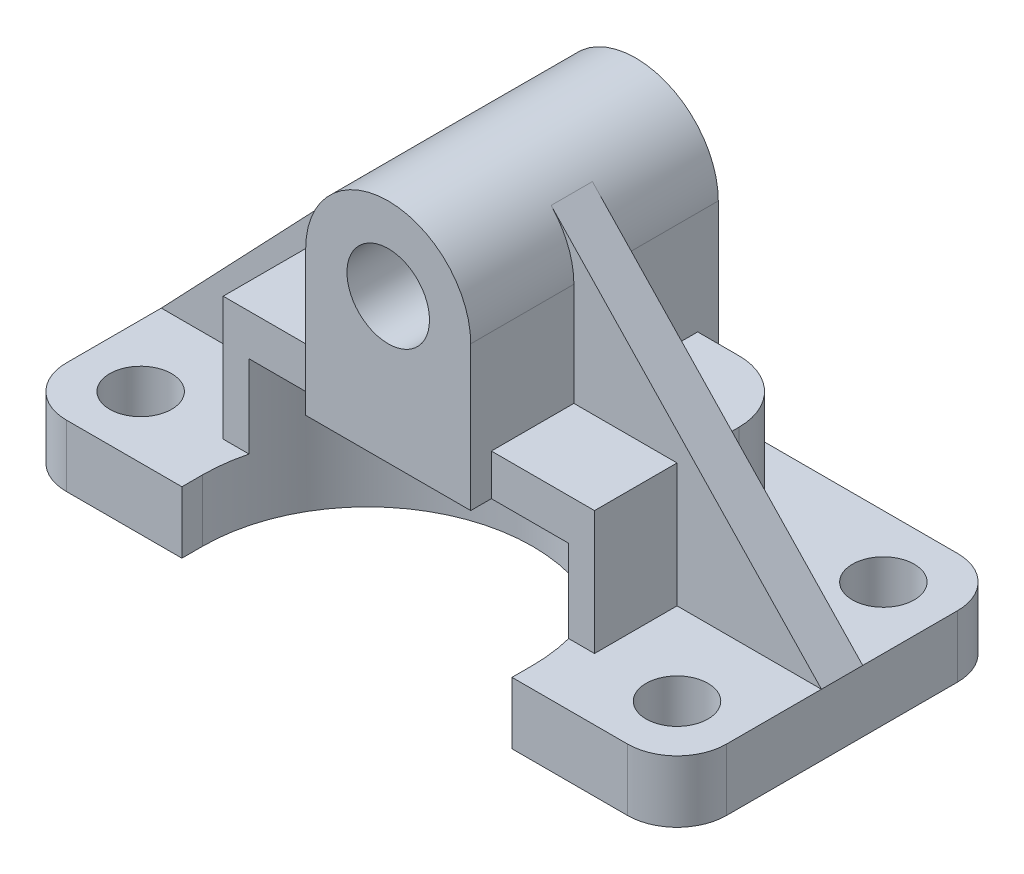
SolidWorks part; units mm, degrees
ref_plane "前视基准面" through (0, 0, 0) normal (0, 0, 1) x (1, 0, 0)
ref_plane "上视基准面" through (0, 0, 0) normal (0, 1, 0) x (1, 0, 0)
ref_plane "右视基准面" through (0, 0, 0) normal (1, 0, 0) x (0, 0, -1)
sketch "草图1" plane through (0, 0, 0) normal (0, 1, 0) x (1, 0, 0)
  line L1 (-80, 40) -> (80, 40)
  line L2 (-80, 40) -> (-80, -40)
  line L3 (-80, -40) -> (80, -40)
  line L4 (80, 40) -> (80, -40)
  line L5 (-80, 40) -> (80, -40) construction
  line L6 (-80, -40) -> (80, 40) construction
  point P0 (0, 0)
  dimension "D1" = 80
  dimension "D2" = 160
extrude "凸台-拉伸1" add sketch "草图1" along normal blind 15
sketch "草图2" plane through (0, 0, 0) normal (0, 1, 0) x (1, 0, 0)
  line L1 (-45, 25) -> (45, 25)
  line L2 (-45, 25) -> (-45, -25)
  line L3 (-45, -25) -> (45, -25)
  line L4 (45, 25) -> (45, -25)
  line L5 (-45, 25) -> (45, -25) construction
  line L6 (-45, -25) -> (45, 25) construction
  point P1 (0, 0)
  dimension "D1" = 50
  dimension "D2" = 90
extrude "凸台-拉伸2" add sketch "草图2" along normal blind 45
sketch "草图6" plane through (0, 0, 0) normal (0, 0, 1) x (1, 0, 0)
  line L0 (0, 15) -> (20, 15)
  line L1 (-80, 15) -> (80, 15) construction
  line L2 (45, 15) -> (-45, 15) construction
  line L3 (0, 15) -> (-20, 15)
  line L4 (-20, 15) -> (-20, 70)
  line L5 (20, 15) -> (20, 70)
  arc A0 (20, 70) -> (-20, 70) centre (0, 70) ccw
  dimension "D1" = 20
extrude "凸台-拉伸8" add sketch "草图6" along normal mid plane 60
sketch "草图7" plane through (0, 0, 0) normal (0, 0, 1) x (1, 0, 0)
  line L0 (-80, 15) -> (-14.4828, 83.7931)
  arc A0 (20, 70) -> (-20, 70) centre (0, 70) ccw construction
rib "筋9" sketch "草图7" sketch "草图7" thickness 10 extrusion direction parallel to sketch draft on no parameters "D1"=10
mirror "镜向1" about plane through (0, 0, 0) normal (1, 0, 0) of "筋9"
sketch "草图8" plane through (0, 0, 0) normal (0, 1, 0) x (1, 0, 0)
  line L0 (-40, -40) -> (40, -40)
  line L1 (-80, -40) -> (80, -40) construction
  line L4 (40, -35) -> (40, -40)
  line L5 (-40, -35) -> (-40, -40)
  arc A0 (40, -35) -> (-40, -35) centre (0, -35) ccw
  dimension "D1" = 40
  dimension "D2" = 80
extrude "切除-拉伸1" cut sketch "草图8" along normal blind 35
sketch "草图10" plane through (0, 0, 0) normal (0, 1, 0) x (1, 0, 0)
  circle A0 centre (-65, 25) radius 7.5
extrude "切除-拉伸2" cut sketch "草图10" along normal through all
mirror "镜向2" about plane through (0, 0, 0) normal (1, 0, 0) of "切除-拉伸2"
mirror "镜向3" about plane through (0, 0, 0) normal (0, 0, 1) of "镜向2", "切除-拉伸2"
fillet "圆角1" radius 12 1 edges at (-80, 7.5, -40)
fillet "圆角2" radius 12 1 edges at (80, 7.5, -40)
fillet "圆角3" radius 12 1 edges at (-80, 7.5, 40)
fillet "圆角4" radius 12 1 edges at (80, 7.5, 40)
fillet "圆角5" radius 15 1 edges at (-45, 30, -25)
fillet "圆角6" radius 15 1 edges at (45, 30, -25)
sketch "草图11" plane through (0, 0, 0) normal (0, 0, 1) x (1, 0, 0)
  circle A0 centre (0, 70) radius 10
  dimension "D1" = 20
extrude "切除-拉伸3" cut sketch "草图11" against normal through all both and the other way through all
